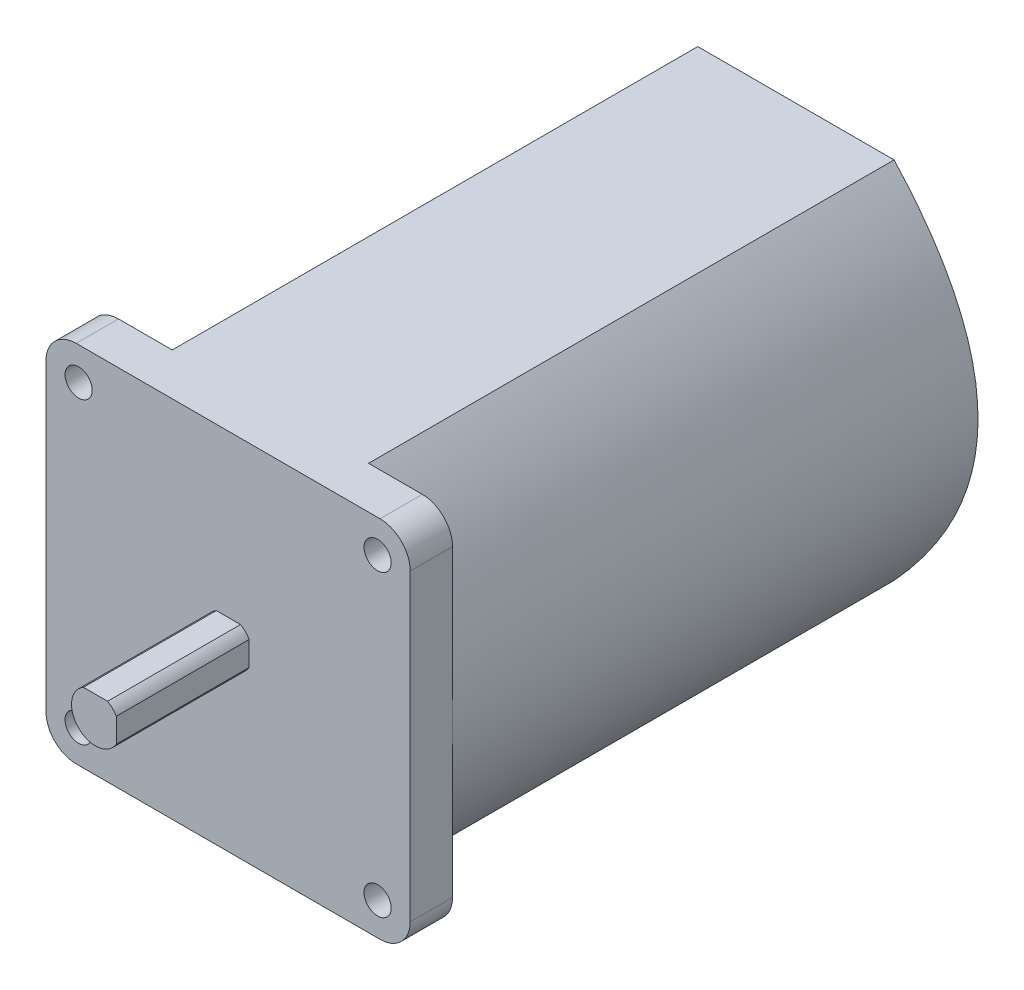
SolidWorks part; units mm, degrees
ref_plane "Front Plane" through (0, 0, 0) normal (0, 0, 1) x (1, 0, 0)
ref_plane "Top Plane" through (0, 0, 0) normal (0, 1, 0) x (1, 0, 0)
ref_plane "Right Plane" through (0, 0, 0) normal (1, 0, 0) x (0, 0, -1)
sketch "Sketch1" plane through (0, 0, 0) normal (0, 0, 1) x (1, 0, 0)
  line L1 (0, 0) -> (32.5, 0)
  line L3 (0, 60.3) -> (32.5, 60.3)
  spline S1 degree 2 poles (0, 60.3) (-27.8, 30.15) (0, 0) knots 0 0 0 1 1 1
  spline S2 degree 2 poles (32.5, 60.3) (60.3, 30.15) (32.5, 0) knots 0 0 0 1 1 1
extrude "Boss-Extrude1" add sketch "Sketch1" along normal blind 87
sketch "Sketch2" plane through (0, 0, 87) normal (0, 0, 1) x (1, 0, 0)
  line L0 (-13.9, 55.3) -> (-13.9, 5)
  line L4 (-8.9, 60.3) -> (41.4, 60.3)
  line L5 (46.4, 55.3) -> (46.4, 5)
  line L6 (41.4, 0) -> (-8.9, 0)
  circle A0 centre (40.9987, 54.8987) radius 2.25
  circle A1 centre (40.9987, 5.4013) radius 2.25
  circle A2 centre (-8.4987, 5.4013) radius 2.25
  circle A3 centre (-8.4987, 54.8987) radius 2.25
  arc A4 (-8.9, 0) -> (-13.9, 5) centre (-8.9, 5) cw
  arc A5 (46.4, 5) -> (41.4, 0) centre (41.4, 5) cw
  arc A6 (41.4, 60.3) -> (46.4, 55.3) centre (41.4, 55.3) cw
  arc A7 (-13.9, 55.3) -> (-8.9, 60.3) centre (-8.9, 55.3) cw
  point P6 (16.25, 30.15)
  dimension "D1" = 5
  dimension "D2" = 4
extrude "Boss-Extrude2" add sketch "Sketch2" along normal blind 7
sketch "Sketch3" plane through (0, 0, 94) normal (0, 0, 1) x (1, 0, 0)
  line L6 (18.3001, 33.5852) -> (14.3001, 33.5852)
  line L8 (19.7353, 32.15) -> (19.7353, 28.15)
  arc A1 (18.3001, 33.5852) -> (19.7353, 32.15) centre (16.3001, 30.15) cw
  arc A2 (14.3001, 33.5852) -> (19.7353, 28.15) centre (16.3001, 30.15) ccw
extrude "Boss-Extrude3" add sketch "Sketch3" along normal blind 22
